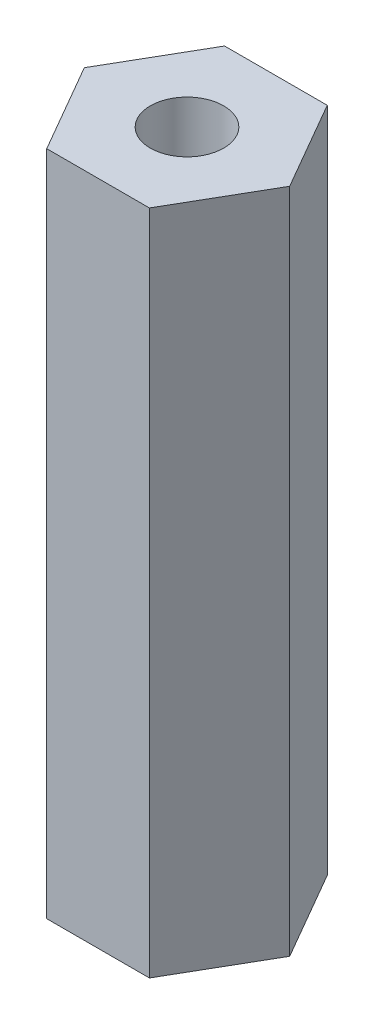
SolidWorks part; units mm, degrees
ref_plane "Alzado" through (0, 0, 0) normal (0, 0, 1) x (1, 0, 0)
ref_plane "Planta" through (0, 0, 0) normal (0, 1, 0) x (1, 0, 0)
ref_plane "Vista lateral" through (0, 0, 0) normal (1, 0, 0) x (0, 0, -1)
sketch "Croquis1" plane through (0, 0, 0) normal (0, 1, 0) x (1, 0, 0)
  line L1 (4.6188, 0) -> (2.3094, 4)
  line L2 (2.3094, 4) -> (-2.3094, 4)
  line L3 (-2.3094, 4) -> (-4.6188, 0)
  line L4 (-4.6188, 0) -> (-2.3094, -4)
  line L5 (-2.3094, -4) -> (2.3094, -4)
  line L6 (2.3094, -4) -> (4.6188, 0)
  circle A0 centre (0, 0) radius 1.65
  circle A1 centre (0, 0) radius 4 construction
  point P3 (3.1177, 0)
  point P11 (0, 0)
  point P12 (2.8252, 1.3185)
  point P13 (3.1177, 0)
  point P14 (0, 0)
  dimension "D1" = 3.3
  dimension "D2" = 8
extrude "Saliente-Extruir1" add sketch "Croquis1" along normal mid plane 30 contours L5 L6 L1 L2 L3 L4 A0
